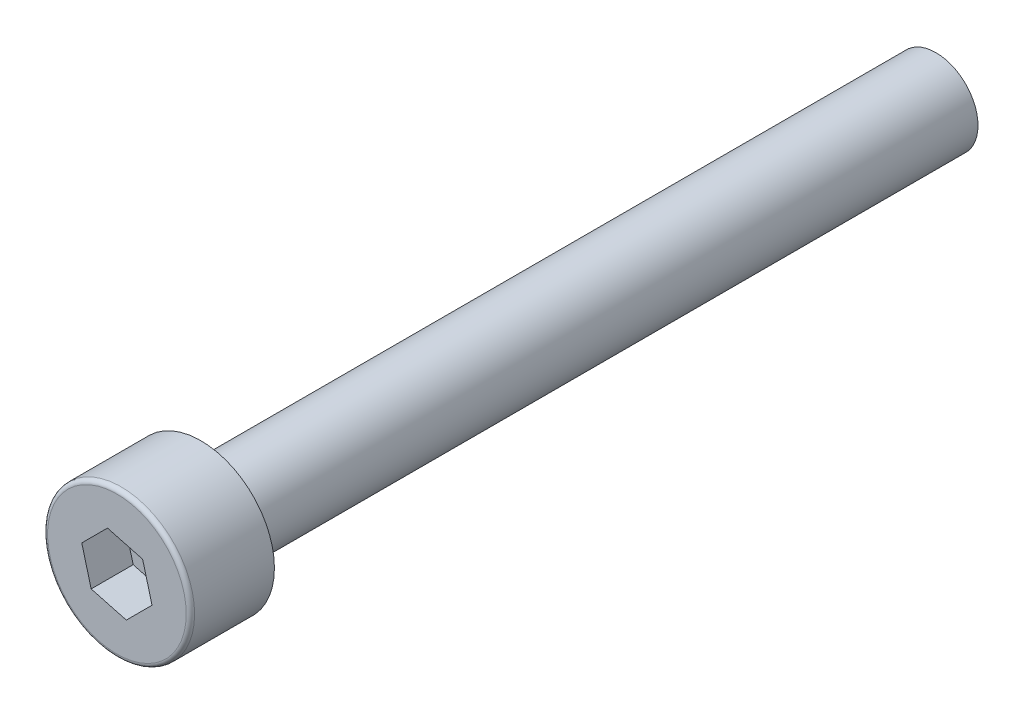
SolidWorks part; units mm, degrees
ref_plane "前视基准面" through (0, 0, 0) normal (0, 0, 1) x (1, 0, 0)
ref_plane "上视基准面" through (0, 0, 0) normal (0, 1, 0) x (1, 0, 0)
ref_plane "右视基准面" through (0, 0, 0) normal (1, 0, 0) x (0, 0, -1)
sketch "草图1" plane through (0, 0, 0) normal (0, 0, 1) x (1, 0, 0)
  circle A0 centre (0, 0) radius 3.5
  dimension "D1" = 7
extrude "凸台-拉伸1" add sketch "草图1" along normal blind 4
sketch "草图2" plane through (0, 0, 4) normal (0, 0, 1) x (1, 0, 0)
  line L1 (-1.2247, -1.2247) -> (0.4483, -1.673)
  line L2 (0.4483, -1.673) -> (1.673, -0.4483)
  line L3 (1.673, -0.4483) -> (1.2247, 1.2247)
  line L4 (1.2247, 1.2247) -> (-0.4483, 1.673)
  line L5 (-0.4483, 1.673) -> (-1.673, 0.4483)
  line L6 (-1.673, 0.4483) -> (-1.2247, -1.2247)
  circle A0 centre (0, 0) radius 1.5 construction
  dimension "D1" = 3
extrude "切除-拉伸1" cut sketch "草图2" against normal blind 2
sketch "草图3" plane through (0, 0, 0) normal (0, 0, -1) x (-1, 0, 0)
  circle A0 centre (0, 0) radius 2
  dimension "D1" = 4
extrude "凸台-拉伸2" add sketch "草图3" along normal blind 35
fillet "圆角1" radius 0.2 1 edges at (3.5, 0, 4)
